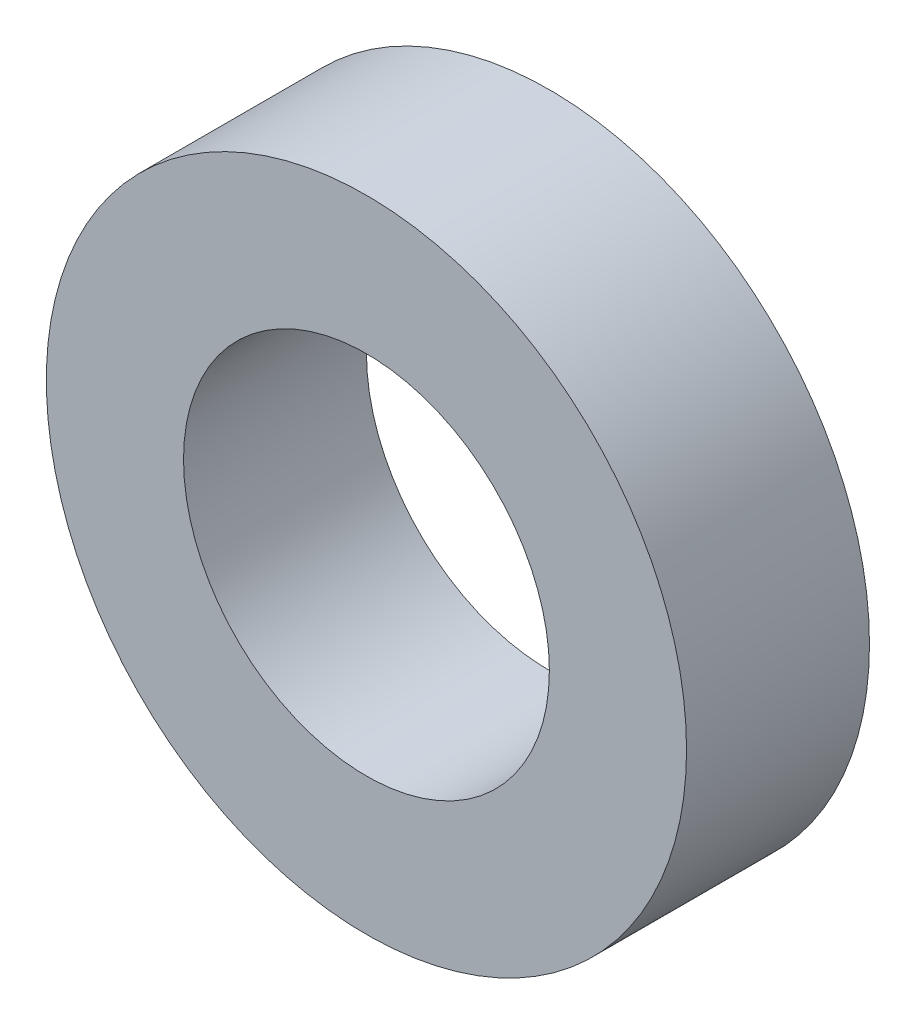
SolidWorks part; units mm, degrees
ref_plane "Front Plane" through (0, 0, 0) normal (0, 0, 1) x (1, 0, 0)
ref_plane "Top Plane" through (0, 0, 0) normal (0, 1, 0) x (1, 0, 0)
ref_plane "Right Plane" through (0, 0, 0) normal (1, 0, 0) x (0, 0, -1)
sketch "Sketch1" plane through (0, 0, 0) normal (0, 0, 1) x (1, 0, 0)
  circle A0 centre (0, 0) radius 4
  circle A1 centre (0, 0) radius 7
  dimension "D1" = 8
  dimension "D2" = 14
extrude "Boss-Extrude1" add sketch "Sketch1" along normal blind 4 contours A1
